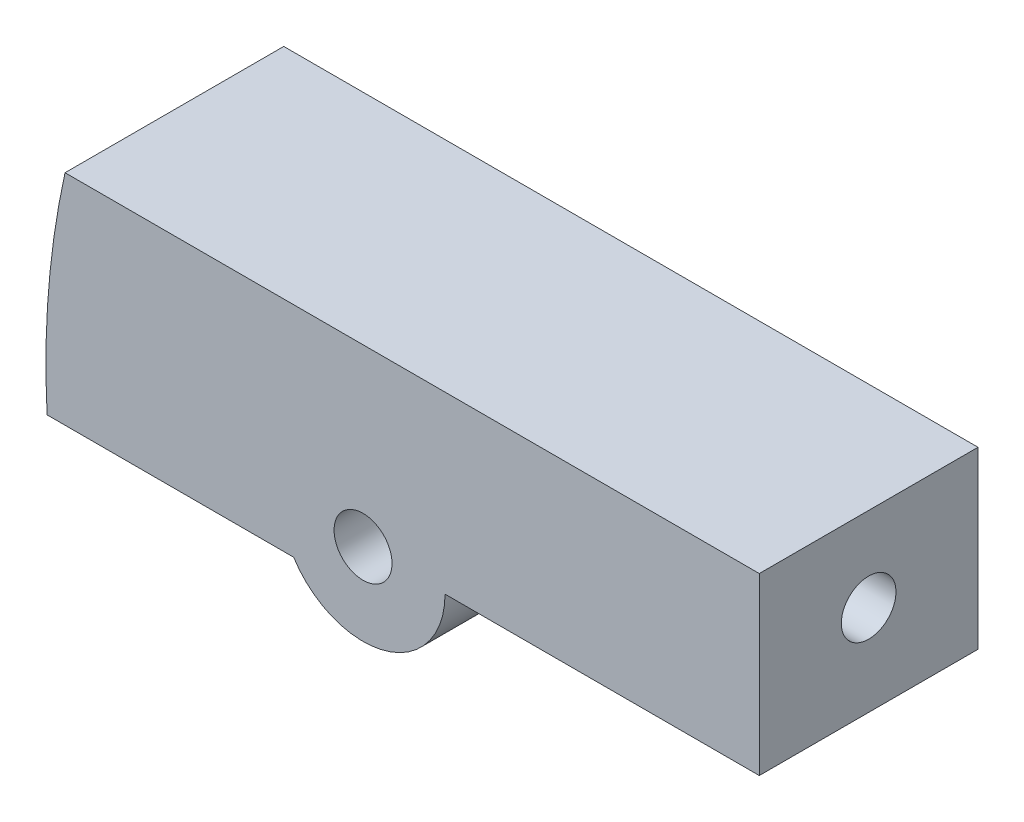
SolidWorks part; units mm, degrees
material "ABS"
ref_plane "Front Plane" through (0, 0, 0) normal (0, 0, 1) x (1, 0, 0)
ref_plane "Top Plane" through (0, 0, 0) normal (0, 1, 0) x (1, 0, 0)
ref_plane "Right Plane" through (0, 0, 0) normal (1, 0, 0) x (0, 0, -1)
sketch "Sketch1" plane through (0, 0, 0) normal (0, 0, 1) x (1, 0, 0)
  line L1 (-65, 21) -> (65, 21) construction
  line L2 (-65, 21) -> (-65, 16) construction
  line L3 (-65, 16) -> (65, 16) construction
  line L4 (65, 21) -> (65, 16) construction
  circle A0 centre (0, 0) radius 76.2 construction
  circle A1 centre (0, 0) radius 4 construction
  circle A2 centre (-45, 0) radius 2.5 construction
  circle A3 centre (45, 0) radius 2.5 construction
  dimension "D1" = 152.4
  dimension "D6" = 8
  dimension "D7" = 5
  dimension "D8" = 5
  dimension "D2" = 130
  dimension "D3" = 5
  dimension "D4" = 65
  dimension "D5" = 21
  dimension "D9" = 45
  dimension "D10" = 45
sketch "Sketch2" plane through (0, 0, 0) normal (0, 0, 1) x (1, 0, 0)
  line L0 (-75.5942, -4) -> (-25.764, -4)
  line L1 (-5.764, 16) -> (-5.764, -4)
  line L2 (-65, 16) -> (65, 16) construction
  line L3 (-5.764, 16) -> (-73.9898, 16)
  line L4 (-37.5, 0) -> (-21.764, 0)
  line L5 (-5.764, -4) -> (-25.764, -4)
  line L6 (-21.764, 0) -> (-5.764, 0)
  circle A1 centre (-45, 0) radius 2.65
  circle A2 centre (0, 0) radius 75.7
  circle A3 centre (0, 0) radius 75.7
  circle A4 centre (-45, 0) radius 7.5
  dimension "D2" = 5.3
  dimension "D3" = 15
  dimension "D4" = 20
  dimension "D5" = 20
  dimension "D1" = 0.5
extrude "Boss-Extrude1" add sketch "Sketch2" along normal mid plane 20
sketch "Sketch3" plane through (0, 0, 0) normal (0, 0, 1) x (1, 0, 0)
  line L0 (-75.2436, 8.3) -> (-55.2761, 8.3)
  line L1 (-70.2436, 13.3) -> (-76.2436, 16.3)
  line L2 (-55.2761, 8.3) -> (-76.2436, 8.3)
  line L4 (-49.2436, 13.3) -> (-76.2436, 13.3)
  line L5 (-76.2436, 8.3) -> (-76.2436, 13.3)
  line L6 (-76.2436, 16.3) -> (-76.2436, 13.3)
  line L7 (-5.764, 16) -> (-73.9898, 16) construction
  line L8 (-48.2436, 12.3) -> (-25.2436, 12.3)
  line L9 (-25.2436, 12.3) -> (-23.7436, 10.8)
  line L10 (-49.2436, 13.3) -> (-48.2436, 12.3)
  line L11 (-23.7436, 10.8) -> (11.2564, 10.8)
  line L12 (-55.2761, 8.3) -> (11.2564, 8.3)
  line L13 (11.2564, 8.3) -> (11.2564, 10.8)
  arc A1 (-73.9898, 16) -> (-75.5942, -4) centre (0, 0) ccw construction
  dimension "D1" = 5
  dimension "D2" = 27
  dimension "D3" = 3
  dimension "D4" = 1
  dimension "D5" = 5
  dimension "D6" = 7.7
  dimension "D7" = 23
  dimension "D8" = 1
  dimension "D9" = 45
  dimension "D10" = 45
  dimension "D11" = 35
  dimension "D12" = 1.5
revolve "Cut-Revolve1" cut sketch "Sketch3" angle 360 about L0
sketch "Sketch4" plane through (0, 0, -10) normal (0, 0, -1) x (-1, 0, 0)
  circle A1 centre (0, 0) radius 75.7 construction
  circle A2 centre (0, 0) radius 75.7
  circle A3 centre (0, 0) radius 74
  point P0 (0, 0)
  dimension "D1" = 148
extrude "Cut-Extrude5" cut sketch "Sketch4" against normal through all
sketch "Sketch5" plane through (0, 0, -10) normal (0, 0, -1) x (-1, 0, 0)
  line L0 (5.764, 16) -> (72.2496, 16) construction
  line L1 (5.764, 0) -> (8.764, 0)
  line L2 (5.764, 0) -> (5.764, 16)
  line L3 (5.764, 16) -> (8.764, 16)
  line L4 (8.764, 0) -> (8.764, 16)
  dimension "D1" = 3
extrude "Cut-Extrude6" cut sketch "Sketch5" against normal through all
